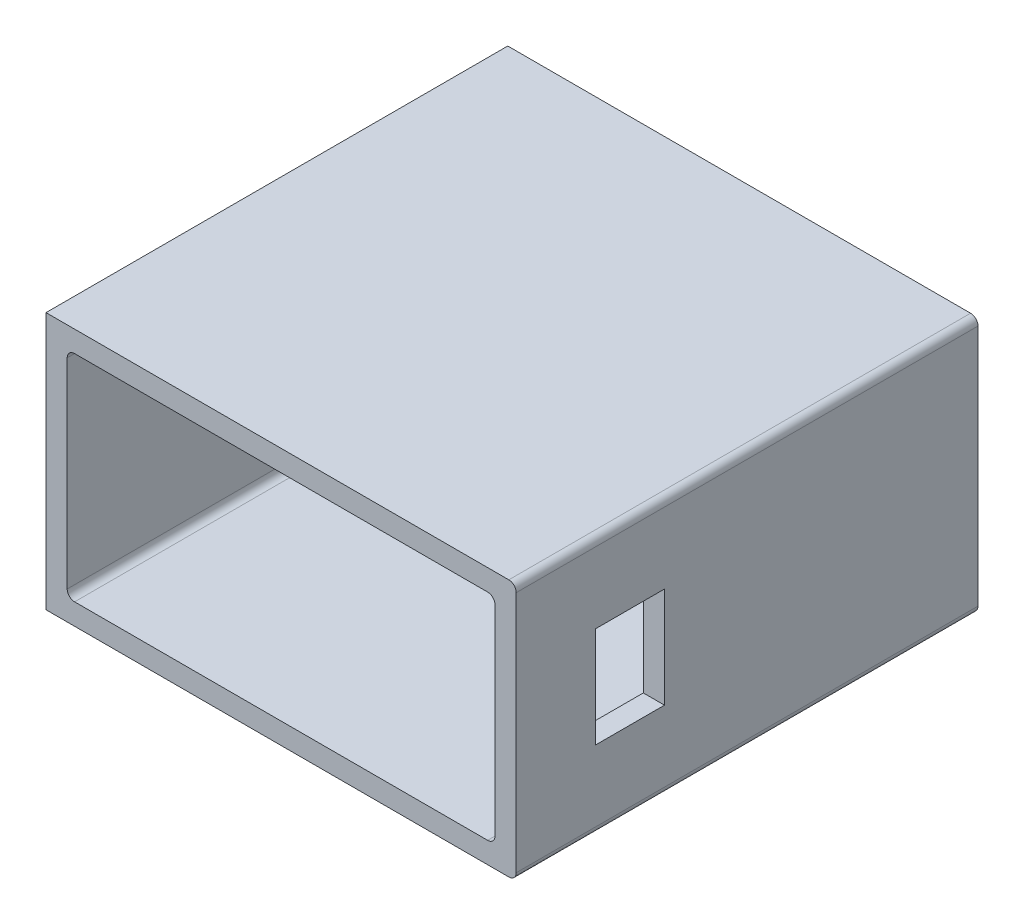
SolidWorks part; units mm, degrees
ref_plane "前视基准面" through (0, 0, 0) normal (0, 0, 1) x (1, 0, 0)
ref_plane "上视基准面" through (0, 0, 0) normal (0, 1, 0) x (1, 0, 0)
ref_plane "右视基准面" through (0, 0, 0) normal (1, 0, 0) x (0, 0, -1)
sketch "草图1" plane through (0, 0, 0) normal (0, 0, 1) x (1, 0, 0)
  line L0 (42.5, 0) -> (90.5, 0) construction
  line L1 (-42.5, 82.5) -> (42.5, 82.5)
  line L2 (-42.5, 82.5) -> (-42.5, -82.5)
  line L3 (-42.5, -82.5) -> (42.5, -82.5)
  line L4 (42.5, 82.5) -> (42.5, -82.5)
  line L5 (-42.5, 82.5) -> (42.5, -82.5) construction
  line L6 (-42.5, -82.5) -> (42.5, 82.5) construction
  line L7 (42.5, 82.5) -> (60.1777, 100.1777) construction
  line L8 (42.5, -82.5) -> (60.1777, -100.1777) construction
  line L9 (-42.5, 0) -> (-90.5, 0) construction
  line L10 (-42.5, -82.5) -> (-60.1777, -100.1777) construction
  line L11 (-42.5, 82.5) -> (-60.1777, 100.1777) construction
  line L12 (58.25, 12.15) -> (102.65, 12.15)
  line L13 (60.25, 10.15) -> (100.65, 10.15)
  line L14 (60.25, 10.15) -> (60.25, -10.15)
  line L15 (60.25, -10.15) -> (100.65, -10.15)
  line L16 (100.65, 10.15) -> (100.65, -10.15)
  line L17 (60.25, 10.15) -> (100.65, -10.15) construction
  line L18 (60.25, -10.15) -> (100.65, 10.15) construction
  line L19 (102.65, 12.15) -> (102.65, -12.15)
  line L20 (58.25, -12.15) -> (102.65, -12.15)
  line L21 (58.25, 12.15) -> (58.25, -12.15)
  line L22 (0, 0) -> (0, 51.9271) construction
  line L23 (-60.25, -10.15) -> (-100.65, 10.15) construction
  line L24 (-60.25, 10.15) -> (-100.65, -10.15) construction
  line L25 (-42.5, 0) -> (-90.5, 0) construction
  line L26 (-58.25, 12.15) -> (-58.25, -12.15)
  line L27 (-58.25, -12.15) -> (-102.65, -12.15)
  line L28 (-102.65, 12.15) -> (-102.65, -12.15)
  line L29 (-100.65, 10.15) -> (-100.65, -10.15)
  line L30 (-60.25, -10.15) -> (-100.65, -10.15)
  line L31 (-60.25, 10.15) -> (-60.25, -10.15)
  line L32 (-60.25, 10.15) -> (-100.65, 10.15)
  line L33 (-58.25, 12.15) -> (-102.65, 12.15)
  point P0 (0, 0)
  point P12 (80.45, 0)
  point P29 (-80.45, 0)
  dimension "D1" = 85
  dimension "D2" = 165
  dimension "D3" = 48
  dimension "D4" = 25
  dimension "D5" = 25
  dimension "D6" = 135
  dimension "D8" = 25
  dimension "D9" = 25
  dimension "D10" = 40.4
  dimension "D11" = 20.3
  dimension "D12" = 10.15
  dimension "D13" = 2
sketch "草图5" plane through (0, 0, 0) normal (0, 0, 1) x (1, 0, 0)
  line L0 (60.1777, 114.5319) -> (74.5319, 100.1777)
  line L1 (74.5319, 100.1777) -> (45.9648, 71.6106)
  line L2 (45.9648, 71.6106) -> (31.6106, 85.9648)
  line L3 (31.6106, 85.9648) -> (60.1777, 114.5319)
  line L4 (60.1777, 100.1777) -> (42.5, 82.5) construction
  line L5 (28.7821, 85.9648) -> (60.1777, 117.3604)
  line L6 (60.1777, 117.3604) -> (77.3604, 100.1777)
  line L7 (77.3604, 100.1777) -> (45.9648, 68.7821)
  line L8 (45.9648, 68.7821) -> (28.7821, 85.9648)
  line L9 (0, 0) -> (28.7821, 0) construction
  line L10 (60.1777, -100.1777) -> (42.5, -82.5) construction
  line L11 (45.9648, -68.7821) -> (28.7821, -85.9648)
  line L12 (77.3604, -100.1777) -> (45.9648, -68.7821)
  line L13 (60.1777, -117.3604) -> (77.3604, -100.1777)
  line L14 (28.7821, -85.9648) -> (60.1777, -117.3604)
  line L15 (31.6106, -85.9648) -> (60.1777, -114.5319)
  line L16 (45.9648, -71.6106) -> (31.6106, -85.9648)
  line L17 (74.5319, -100.1777) -> (45.9648, -71.6106)
  line L18 (60.1777, -114.5319) -> (74.5319, -100.1777)
  line L19 (0, 0) -> (0, 63.0262) construction
  line L20 (-60.1777, -100.1777) -> (-42.5, -82.5) construction
  line L21 (-60.1777, 100.1777) -> (-42.5, 82.5) construction
  line L22 (-60.1777, -114.5319) -> (-74.5319, -100.1777)
  line L23 (-74.5319, -100.1777) -> (-45.9648, -71.6106)
  line L24 (-45.9648, -71.6106) -> (-31.6106, -85.9648)
  line L25 (-31.6106, -85.9648) -> (-60.1777, -114.5319)
  line L26 (-28.7821, -85.9648) -> (-60.1777, -117.3604)
  line L27 (-60.1777, -117.3604) -> (-77.3604, -100.1777)
  line L28 (-77.3604, -100.1777) -> (-45.9648, -68.7821)
  line L29 (-45.9648, -68.7821) -> (-28.7821, -85.9648)
  line L30 (-45.9648, 68.7821) -> (-28.7821, 85.9648)
  line L31 (-77.3604, 100.1777) -> (-45.9648, 68.7821)
  line L32 (-60.1777, 117.3604) -> (-77.3604, 100.1777)
  line L33 (-28.7821, 85.9648) -> (-60.1777, 117.3604)
  line L34 (-31.6106, 85.9648) -> (-60.1777, 114.5319)
  line L35 (-45.9648, 71.6106) -> (-31.6106, 85.9648)
  line L36 (-74.5319, 100.1777) -> (-45.9648, 71.6106)
  line L37 (-60.1777, 114.5319) -> (-74.5319, 100.1777)
  dimension "D1" = 40.4
  dimension "D2" = 20.3
  dimension "D3" = 10.15
  dimension "D4" = 2
extrude "凸台-拉伸5" add sketch "草图1" along normal blind 42 contours L26 L33 L28 L27 L32 L31 L30 L29 | L12 L21 L20 L19 L13 L16 L15 L14 | L2 L3 L4 L1
extrude "凸台-拉伸6" add sketch "草图5" along normal blind 42
sketch "草图6" plane through (0, 0, 0) normal (0, 0, -1) x (-1, 0, 0)
  line L0 (-77.3604, 100.1777) -> (-60.1777, 117.3604)
  line L1 (-60.1777, 117.3604) -> (-28.7821, 85.9648)
  line L2 (-28.7821, 85.9648) -> (-45.9648, 68.7821)
  line L3 (-45.9648, 68.7821) -> (-77.3604, 100.1777)
  line L4 (-60.1777, 100.1777) -> (-55.3693, 95.3693) construction
  line L5 (-42.5, 82.5) -> (-60.1777, 100.1777) construction
  line L6 (-55.3693, 95.3693) -> (-61.0262, 89.7125) construction
  line L7 (-46.0214, 86.0214) -> (-50.9711, 81.0716) construction
  line L8 (-60.1777, 100.1777) -> (-41.0716, 81.0716) construction
  line L9 (-58.25, 12.15) -> (-58.25, -12.15)
  line L10 (-58.25, -12.15) -> (-102.65, -12.15)
  line L11 (-70.48, 0) -> (-70.48, -7) construction
  line L12 (-102.65, 12.15) -> (-58.25, 12.15)
  line L13 (-90.5, 0) -> (-83.7, 0) construction
  line L14 (-83.7, 0) -> (-83.7, -8) construction
  line L15 (-102.65, -12.15) -> (-102.65, 12.15)
  line L16 (-90.5, 0) -> (-63.48, 0) construction
  line L17 (0, 0) -> (28.8174, 0) construction
  line L18 (-60.1777, -100.1777) -> (-41.0716, -81.0716) construction
  line L19 (-46.0214, -86.0214) -> (-50.9711, -81.0716) construction
  line L20 (-55.3693, -95.3693) -> (-61.0262, -89.7125) construction
  line L21 (-60.1777, -100.1777) -> (-55.3693, -95.3693) construction
  line L22 (-45.9648, -68.7821) -> (-77.3604, -100.1777)
  line L23 (-28.7821, -85.9648) -> (-45.9648, -68.7821)
  line L24 (-60.1777, -117.3604) -> (-28.7821, -85.9648)
  line L25 (-77.3604, -100.1777) -> (-60.1777, -117.3604)
  line L26 (0, 0) -> (0, 41.0971) construction
  line L27 (0, 0) -> (0, 51.9271) construction
  line L28 (60.1777, -100.1777) -> (55.3693, -95.3693) construction
  line L29 (55.3693, -95.3693) -> (61.0262, -89.7125) construction
  line L30 (46.0214, -86.0214) -> (50.9711, -81.0716) construction
  line L31 (60.1777, -100.1777) -> (41.0716, -81.0716) construction
  line L32 (90.5, 0) -> (63.48, 0) construction
  line L33 (83.7, 0) -> (83.7, -8) construction
  line L34 (90.5, 0) -> (83.7, 0) construction
  line L35 (70.48, 0) -> (70.48, -7) construction
  line L36 (60.1777, 100.1777) -> (41.0716, 81.0716) construction
  line L37 (46.0214, 86.0214) -> (50.9711, 81.0716) construction
  line L38 (55.3693, 95.3693) -> (61.0262, 89.7125) construction
  line L39 (60.1777, 100.1777) -> (55.3693, 95.3693) construction
  line L40 (77.3604, -100.1777) -> (60.1777, -117.3604)
  line L41 (60.1777, -117.3604) -> (28.7821, -85.9648)
  line L42 (28.7821, -85.9648) -> (45.9648, -68.7821)
  line L43 (45.9648, -68.7821) -> (77.3604, -100.1777)
  line L44 (102.65, -12.15) -> (102.65, 12.15)
  line L45 (102.65, 12.15) -> (58.25, 12.15)
  line L46 (58.25, -12.15) -> (102.65, -12.15)
  line L47 (58.25, 12.15) -> (58.25, -12.15)
  line L48 (45.9648, 68.7821) -> (77.3604, 100.1777)
  line L49 (28.7821, 85.9648) -> (45.9648, 68.7821)
  line L50 (60.1777, 117.3604) -> (28.7821, 85.9648)
  line L51 (77.3604, 100.1777) -> (60.1777, 117.3604)
  circle A0 centre (-60.1777, 100.1777) radius 6.75
  circle A1 centre (-61.0262, 89.7125) radius 0.8
  circle A2 centre (-50.9711, 81.0716) radius 0.8
  circle A3 centre (-41.0716, 81.0716) radius 0.8
  circle A4 centre (-41.0716, 90.9711) radius 0.8
  circle A5 centre (-49.7125, 101.0262) radius 0.8
  circle A6 centre (-70.48, -7) radius 0.8
  circle A7 centre (-63.48, 0) radius 0.8
  circle A8 centre (-90.5, 0) radius 6.75
  circle A9 centre (-83.7, -8) radius 0.8
  circle A10 centre (-70.48, 7) radius 0.8
  circle A11 centre (-83.7, 8) radius 0.8
  circle A12 centre (-49.7125, -101.0262) radius 0.8
  circle A13 centre (-41.0716, -90.9711) radius 0.8
  circle A14 centre (-41.0716, -81.0716) radius 0.8
  circle A15 centre (-50.9711, -81.0716) radius 0.8
  circle A16 centre (-61.0262, -89.7125) radius 0.8
  circle A17 centre (-60.1777, -100.1777) radius 6.75
  circle A18 centre (60.1777, -100.1777) radius 6.75
  circle A19 centre (61.0262, -89.7125) radius 0.8
  circle A20 centre (50.9711, -81.0716) radius 0.8
  circle A21 centre (41.0716, -81.0716) radius 0.8
  circle A22 centre (41.0716, -90.9711) radius 0.8
  circle A23 centre (49.7125, -101.0262) radius 0.8
  circle A24 centre (83.7, 8) radius 0.8
  circle A25 centre (70.48, 7) radius 0.8
  circle A26 centre (83.7, -8) radius 0.8
  circle A27 centre (90.5, 0) radius 6.75
  circle A28 centre (63.48, 0) radius 0.8
  circle A29 centre (70.48, -7) radius 0.8
  circle A30 centre (49.7125, 101.0262) radius 0.8
  circle A31 centre (41.0716, 90.9711) radius 0.8
  circle A32 centre (41.0716, 81.0716) radius 0.8
  circle A33 centre (50.9711, 81.0716) radius 0.8
  circle A34 centre (61.0262, 89.7125) radius 0.8
  circle A35 centre (60.1777, 100.1777) radius 6.75
  dimension "D1" = 13.5
  dimension "D4" = 1.6
  dimension "D7" = 1.6
  dimension "D9" = 1.6
  dimension "D2" = 6.8
  dimension "D3" = 8
  dimension "D5" = 7
  dimension "D6" = 20.02
  dimension "D8" = 27.02
extrude "凸台-拉伸8" add sketch "草图6" along normal blind 1.6
fillet "圆角1" radius 0.7 4 edges at (31.6106, 85.9648, 21) (45.9648, 71.6106, 21) (60.1777, 114.5319, 21) (74.5319, 100.1777, 21)
fillet "圆角2" radius 0.7 4 edges at (-74.5319, 100.1777, 21) (-60.1777, 114.5319, 21) (-45.9648, 71.6106, 21) (-31.6106, 85.9648, 21)
fillet "圆角3" radius 0.7 4 edges at (-60.25, -10.15, 21) (-100.65, -10.15, 21) (-100.65, 10.15, 21) (-60.25, 10.15, 21)
fillet "圆角4" radius 0.7 4 edges at (-60.1777, -114.5319, 21) (-74.5319, -100.1777, 21) (-45.9648, -71.6106, 21) (-31.6106, -85.9648, 21)
fillet "圆角5" radius 0.7 4 edges at (60.1777, -114.5319, 21) (74.5319, -100.1777, 21) (45.9648, -71.6106, 21) (31.6106, -85.9648, 21)
fillet "圆角6" radius 0.7 4 edges at (60.25, 10.15, 21) (60.25, -10.15, 21) (100.65, -10.15, 21) (100.65, 10.15, 21)
sketch "草图7" plane through (0, 0, -1.6) normal (0, 0, -1) x (-1, 0, 0)
  line L0 (0, 0) -> (0, -53.3863) construction
  circle A4 centre (83.7, 8) radius 2
  circle A5 centre (83.7, -8) radius 2
  circle A6 centre (61.0262, -89.7125) radius 2
  circle A7 centre (49.7125, -101.0262) radius 2
  circle A8 centre (-49.7125, -101.0262) radius 2
  circle A9 centre (-61.0262, -89.7125) radius 2
  circle A10 centre (-83.7, -8) radius 2
  circle A11 centre (-83.7, 8) radius 2
  circle A14 centre (-61.0262, 89.7125) radius 2
  circle A15 centre (-49.7125, 101.0262) radius 2
  circle A16 centre (49.7125, 101.0262) radius 2
  circle A17 centre (61.0262, 89.7125) radius 2
  dimension "D3" = 4
  dimension "D4" = 4
  dimension "D5" = 4
  dimension "D6" = 4
  dimension "D7" = 4
  dimension "D8" = 4
  dimension "D9" = 4
  dimension "D10" = 4
extrude "切除-拉伸2" cut sketch "草图7" against normal blind 0.7
sketch "草图8" plane through (-88.769, -88.769, 0) normal (-0.7071, -0.7071, 0) x (0, 0, 1)
  line L0 (-1.6, -28.2843) -> (42, -28.2843) construction
  line L1 (-1.6, -40.4343) -> (-1.6, -16.1343) construction
  line L2 (42, -16.1343) -> (42, -40.4343) construction
  line L4 (28, -23.5343) -> (34.5, -23.5343)
  line L5 (28, -23.5343) -> (28, -33.0343)
  line L6 (28, -33.0343) -> (34.5, -33.0343)
  line L7 (34.5, -23.5343) -> (34.5, -33.0343)
  dimension "D1" = 7.5
  dimension "D2" = 9.5
  dimension "D3" = 6.5
extrude "切除-拉伸3" cut sketch "草图8" against normal blind 9.8
sketch "草图9" plane through (-102.65, 0, 0) normal (-1, 0, 0) x (0, 0, 1)
  line L0 (42, 12.15) -> (42, -12.15) construction
  line L1 (28, 4.75) -> (34.5, 4.75)
  line L2 (28, 4.75) -> (28, -4.75)
  line L3 (28, -4.75) -> (34.5, -4.75)
  line L4 (34.5, 4.75) -> (34.5, -4.75)
  line L5 (42, 0) -> (20.8942, 0) construction
  dimension "D1" = 6.5
  dimension "D2" = 7.5
  dimension "D3" = 9.5
extrude "切除-拉伸4" cut sketch "草图9" against normal blind 9.8
sketch "草图10" plane through (-88.769, 88.769, 0) normal (-0.7071, 0.7071, 0) x (0, 0, 1)
  line L0 (42, 28.2843) -> (10.5352, 28.2843) construction
  line L1 (42, 40.4343) -> (42, 16.1343) construction
  line L3 (28, 33.0559) -> (34.5, 33.0559)
  line L4 (28, 33.0559) -> (28, 23.5559)
  line L5 (28, 23.5559) -> (34.5, 23.5559)
  line L6 (34.5, 33.0559) -> (34.5, 23.5559)
  dimension "D1" = 7.5
  dimension "D2" = 6.5
  dimension "D3" = 9.5
extrude "切除-拉伸5" cut sketch "草图10" against normal blind 9.8
sketch "草图11" plane through (88.769, 88.769, 0) normal (0.7071, 0.7071, 0) x (0, 0, -1)
  line L0 (1.6, 40.4343) -> (1.6, 16.1343) construction
  line L1 (-34.5, 33.0343) -> (-28, 33.0343)
  line L2 (-34.5, 33.0343) -> (-34.5, 23.5343)
  line L3 (-34.5, 23.5343) -> (-28, 23.5343)
  line L4 (-28, 33.0343) -> (-28, 23.5343)
  line L5 (1.6, 28.2843) -> (-24.8278, 28.2843) construction
  line L6 (-42, 16.1343) -> (-42, 40.4343) construction
  dimension "D1" = 6.5
  dimension "D2" = 9.5
  dimension "D3" = 7.5
extrude "切除-拉伸6" cut sketch "草图11" against normal blind 9.8
sketch "草图12" plane through (102.65, 0, 0) normal (1, 0, 0) x (0, 0, -1)
  line L0 (-42, 12.15) -> (-42, -12.15) construction
  line L1 (-34.5, 4.75) -> (-28, 4.75)
  line L2 (-34.5, 4.75) -> (-34.5, -4.75)
  line L3 (-34.5, -4.75) -> (-28, -4.75)
  line L4 (-28, 4.75) -> (-28, -4.75)
  line L5 (-42, 0) -> (-21.0394, 0) construction
  dimension "D1" = 6.5
  dimension "D2" = 7.5
  dimension "D3" = 9.5
extrude "切除-拉伸7" cut sketch "草图12" against normal blind 9.8
sketch "草图13" plane through (88.769, -88.769, 0) normal (0.7071, -0.7071, 0) x (0, 0, -1)
  line L0 (-42, -28.2843) -> (-21.5674, -28.2843) construction
  line L1 (-42, -40.4343) -> (-42, -16.1343) construction
  line L3 (-34.5, -23.5343) -> (-28, -23.5343)
  line L4 (-34.5, -23.5343) -> (-34.5, -33.0343)
  line L5 (-34.5, -33.0343) -> (-28, -33.0343)
  line L6 (-28, -23.5343) -> (-28, -33.0343)
  dimension "D1" = 6.5
  dimension "D2" = 7.5
  dimension "D3" = 9.5
extrude "切除-拉伸8" cut sketch "草图13" against normal blind 9.8
fillet "圆角7" radius 0.7 2 edges at (-77.3604, 100.1777, 20.2) (-60.1777, 117.3604, 20.2)
fillet "圆角8" radius 0.7 2 edges at (-102.65, -12.15, 20.2) (-102.65, 12.15, 20.2)
fillet "圆角9" radius 0.7 2 edges at (-60.1777, -117.3604, 20.2) (-77.3604, -100.1777, 20.2)
fillet "圆角10" radius 0.7 2 edges at (77.3604, -100.1777, 20.2) (60.1777, -117.3604, 20.2)
fillet "圆角11" radius 0.7 2 edges at (102.65, 12.15, 20.2) (102.65, -12.15, 20.2)
fillet "圆角12" radius 0.7 2 edges at (60.1777, 117.3604, 20.2) (77.3604, 100.1777, 20.2)
sketch "草图14" plane through (0, 0, 42) normal (0, 0, 1) x (1, 0, 0)
  line L0 (58.25, 12.15) -> (42.5, 24.8626)
  line L1 (-25.3173, 82.5) -> (25.3173, 82.5)
  line L2 (-42.5, 65.3173) -> (-42.5, 24.8626)
  line L3 (-25.3173, -82.5) -> (25.3173, -82.5)
  line L4 (42.5, 65.3173) -> (42.5, 24.8626)
  line L5 (58.25, -12.15) -> (58.25, 12.15)
  line L6 (58.25, -12.15) -> (102.65, -12.15) construction
  line L7 (58.25, -12.15) -> (42.5, -24.8626)
  line L8 (0, 0) -> (25.9785, 0) construction
  line L9 (0, 0) -> (0, 16.1012) construction
  line L11 (0, 0) -> (0, 51.9271) construction
  line L12 (-28.7821, 85.9648) -> (-25.3173, 82.5)
  line L13 (-28.7821, 85.9648) -> (-45.9648, 68.7821)
  line L14 (-45.9648, 68.7821) -> (-42.5, 65.3173)
  line L15 (28.7821, 85.9648) -> (25.3173, 82.5)
  line L16 (28.7821, 85.9648) -> (45.9648, 68.7821)
  line L17 (45.9648, 68.7821) -> (42.5, 65.3173)
  line L18 (45.9648, -68.7821) -> (42.5, -65.3173)
  line L19 (28.7821, -85.9648) -> (25.3173, -82.5)
  line L20 (28.7821, -85.9648) -> (45.9648, -68.7821)
  line L21 (-45.9648, -68.7821) -> (-42.5, -65.3173)
  line L22 (-28.7821, -85.9648) -> (-45.9648, -68.7821)
  line L23 (-28.7821, -85.9648) -> (-25.3173, -82.5)
  line L24 (-58.25, -12.15) -> (-42.5, -24.8626)
  line L25 (-58.25, -12.15) -> (-58.25, 12.15)
  line L26 (-58.25, 12.15) -> (-42.5, 24.8626)
  line L27 (-42.5, -24.8626) -> (-42.5, -65.3173)
  line L28 (42.5, -24.8626) -> (42.5, -65.3173)
extrude "凸台-拉伸9" add sketch "草图14" against normal blind 3
sketch "草图19" plane through (0, 0, 39) normal (0, 0, -1) x (-1, 0, 0)
  line L0 (-50.2075, 73.0248) -> (-50.2075, 33.0248)
  line L1 (-76.8654, 99.6827) -> (-45.9648, 68.7821) construction
  line L2 (-50.2075, 33.0248) -> (-58.25, 26.5333)
  line L3 (-58.25, 26.5333) -> (-58.25, 12.15)
  line L4 (-58.25, 12.15) -> (-42.5, 24.8626) construction
  line L5 (-50.2075, 73.0248) -> (-45.9648, 68.7821)
  line L6 (-45.9648, 68.7821) -> (-28.7821, 85.9648)
  line L7 (-28.7821, 85.9648) -> (28.7821, 85.9648)
  line L8 (28.7821, 85.9648) -> (45.9648, 68.7821)
  line L9 (0, 85.9648) -> (0, -134.9503) construction
  line L10 (0, 0) -> (40.7748, 0) construction
  line L11 (28.7821, -85.9648) -> (45.9648, -68.7821)
  line L12 (-28.7821, -85.9648) -> (28.7821, -85.9648)
  line L13 (-45.9648, -68.7821) -> (-28.7821, -85.9648)
  line L14 (-50.2075, -73.0248) -> (-45.9648, -68.7821)
  line L15 (-58.25, -26.5333) -> (-58.25, -12.15)
  line L16 (-50.2075, -33.0248) -> (-58.25, -26.5333)
  line L17 (-50.2075, -73.0248) -> (-50.2075, -33.0248)
  line L18 (50.2075, -73.0248) -> (45.9648, -68.7821)
  line L19 (50.2075, -73.0248) -> (50.2075, -33.0248)
  line L20 (50.2075, -33.0248) -> (58.25, -26.5333)
  line L21 (58.25, -26.5333) -> (58.25, -12.15)
  line L22 (58.25, 26.5333) -> (58.25, 12.15)
  line L23 (50.2075, 33.0248) -> (58.25, 26.5333)
  line L24 (50.2075, 73.0248) -> (50.2075, 33.0248)
  line L25 (50.2075, 73.0248) -> (45.9648, 68.7821)
  line L26 (58.25, 12.15) -> (58.25, -12.15)
  line L27 (-58.25, 12.15) -> (-58.25, -12.15)
  dimension "D1" = 6
  dimension "D2" = 40
extrude "凸台-拉伸11" add sketch "草图19" against normal up to vertex (3 mm away)
sketch "草图20" plane through (0, 0, 39) normal (0, 0, -1) x (-1, 0, 0)
  line L0 (-28.7821, 85.9648) -> (-35.7821, 92.9648)
  line L1 (-28.7821, 85.9648) -> (-59.6827, 116.8654) construction
  line L2 (-35.7821, 92.9648) -> (35.7821, 92.9648)
  line L3 (59.6827, 116.8654) -> (28.7821, 85.9648) construction
  line L4 (35.7821, 92.9648) -> (28.7821, 85.9648)
  line L5 (28.7821, 85.9648) -> (-28.7821, 85.9648)
  line L6 (-58.25, 0) -> (41.7659, 0) construction
  line L7 (-58.25, -12.15) -> (-58.25, 12.15) construction
  line L8 (-28.7821, -85.9648) -> (-35.7821, -92.9648)
  line L9 (35.7821, -92.9648) -> (28.7821, -85.9648)
  line L10 (-35.7821, -92.9648) -> (35.7821, -92.9648)
  line L11 (28.7821, -85.9648) -> (-28.7821, -85.9648)
  dimension "D1" = 7
extrude "凸台-拉伸12" add sketch "草图20" against normal up to vertex (3 mm away)
sketch "草图21" plane through (0, 0, 42) normal (0, 0, 1) x (1, 0, 0)
  line L0 (-58.25, 26.5333) -> (-63.25, 22.4975)
  line L1 (-63.25, 22.4975) -> (-63.25, 12.15)
  line L2 (-58.25, 12.15) -> (-101.95, 12.15) construction
  line L3 (-63.25, 12.15) -> (-58.25, 12.15)
  line L4 (-58.25, 12.15) -> (-58.25, 26.5333)
  line L5 (-58.25, 26.5333) -> (-50.2075, 33.0248) construction
  line L6 (-60.25, 0) -> (-30.6569, 0) construction
  line L7 (-60.25, 9.45) -> (-60.25, -9.45) construction
  line L8 (-63.25, -22.4975) -> (-63.25, -12.15)
  line L9 (-63.25, -12.15) -> (-58.25, -12.15)
  line L10 (-58.25, -12.15) -> (-58.25, -26.5333)
  line L11 (-58.25, -26.5333) -> (-63.25, -22.4975)
  line L12 (0, 0) -> (0, -27.8132) construction
  line L13 (60.25, 0) -> (30.6569, 0) construction
  line L14 (58.25, -26.5333) -> (63.25, -22.4975)
  line L15 (58.25, -12.15) -> (58.25, -26.5333)
  line L16 (63.25, -12.15) -> (58.25, -12.15)
  line L17 (63.25, -22.4975) -> (63.25, -12.15)
  line L18 (58.25, 12.15) -> (58.25, 26.5333)
  line L19 (63.25, 12.15) -> (58.25, 12.15)
  line L20 (63.25, 22.4975) -> (63.25, 12.15)
  line L21 (58.25, 26.5333) -> (63.25, 22.4975)
  dimension "D1" = 5
extrude "凸台-拉伸13" add sketch "草图21" against normal up to vertex
sketch "草图22" plane through (0, 0, 42) normal (0, 0, 1) x (1, 0, 0)
  line L1 (-37.5, -80) -> (37.5, -80)
  line L2 (-37.5, -80) -> (-37.5, 80)
  line L3 (-37.5, 80) -> (37.5, 80)
  line L4 (37.5, -80) -> (37.5, 80)
  line L5 (-37.5, -80) -> (37.5, 80) construction
  line L6 (-37.5, 80) -> (37.5, -80) construction
  point P0 (0, 0)
  dimension "D1" = 160
  dimension "D2" = 75
sketch "草图23" plane through (0, 0, 39) normal (0, 0, -1) x (-1, 0, 0)
  line L0 (-68.6108, 12.15) -> (-58.25, 12.15)
  line L1 (-58.25, 12.15) -> (-101.95, 12.15) construction
  line L2 (-58.25, 12.15) -> (-58.25, -12.15)
  line L3 (-58.25, -12.15) -> (-68.6108, -12.15)
  line L4 (-101.95, -12.15) -> (-58.25, -12.15) construction
  line L5 (-68.6108, -12.15) -> (-90.7098, -134.478)
  line L6 (-90.7098, -134.478) -> (134.0652, -134.478)
  line L7 (134.0652, -134.478) -> (122.6899, 131.2478)
  line L8 (122.6899, 131.2478) -> (-101.95, 131.2478)
  line L9 (-101.95, 131.2478) -> (-68.6108, 12.15)
extrude "切除-拉伸9" cut sketch "草图23" against normal blind 10
sketch "草图24" plane through (0, 0, -1.6) normal (0, 0, -1) x (-1, 0, 0)
  line L1 (-58.25, 12.15) -> (-102.65, 12.15)
  line L2 (-58.25, 12.15) -> (-58.25, -12.15)
  line L3 (-58.25, -12.15) -> (-102.65, -12.15)
  line L4 (-102.65, 12.15) -> (-102.65, -12.15)
  dimension "D1" = 24.3
  dimension "D2" = 44.4
